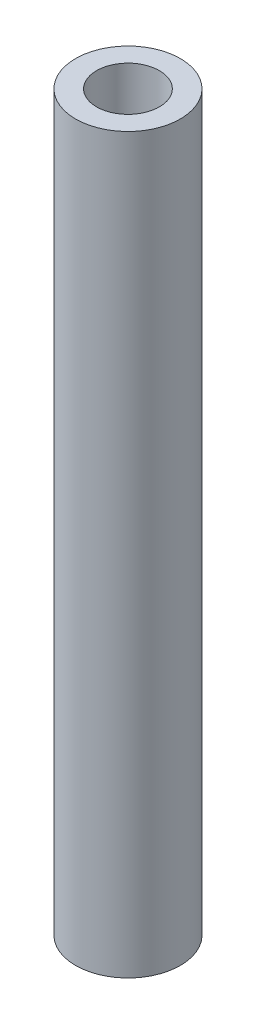
SolidWorks part; units mm, degrees
ref_plane "Alzado" through (0, 0, 0) normal (0, 0, 1) x (1, 0, 0)
ref_plane "Planta" through (0, 0, 0) normal (0, 1, 0) x (1, 0, 0)
ref_plane "Vista lateral" through (0, 0, 0) normal (1, 0, 0) x (0, 0, -1)
sketch "Croquis1" plane through (0, 0, 0) normal (0, 1, 0) x (1, 0, 0)
  circle A0 centre (0, 0) radius 2.5
  dimension "D1" = 5
extrude "Saliente-Extruir1" add sketch "Croquis1" along normal blind 35
sketch "Croquis2" plane through (0, 35, 0) normal (0, 1, 0) x (1, 0, 0)
  circle A0 centre (0, 0) radius 1.5
  dimension "D1" = 3
extrude "Cortar-Extruir1" cut sketch "Croquis2" against normal blind 35 contours A0
